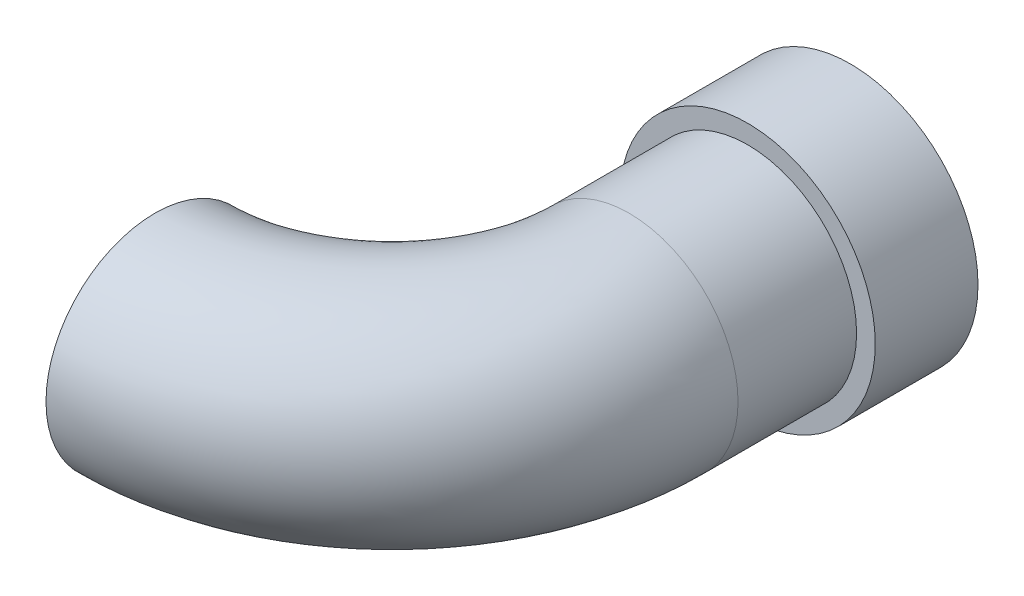
SolidWorks part; units mm, degrees
material "AISI 321 Annealed Stainless Steel (SS)"
ref_plane "Front Plane" through (0, 0, 0) normal (0, 0, 1) x (1, 0, 0)
ref_plane "Top Plane" through (0, 0, 0) normal (0, 1, 0) x (1, 0, 0)
ref_plane "Right Plane" through (0, 0, 0) normal (1, 0, 0) x (0, 0, -1)
sketch "Sketch1" plane through (0, 0, 0) normal (0, 0, 1) x (1, 0, 0)
  circle A0 centre (0, 0) radius 20.5
  circle A1 centre (0, 0) radius 17.5
  dimension "D1" = 41
  dimension "D2" = 3
extrude "Boss-Extrude1" add sketch "Sketch1" along normal blind 16.51
ref_plane "Plane1" through (0, 0, 10.16) normal (0, 0, 1) x (1, 0, 0)
sketch "Sketch2" plane through (0, 0, 10.16) normal (0, 0, 1) x (1, 0, 0)
  circle A0 centre (0, 0) radius 17.5
  circle A1 centre (0, 0) radius 15.5
  dimension "D1" = 2
  dimension "D2" = 35
sketch "Sketch4" plane through (0, 0, 10.16) normal (0, 0, 1) x (1, 0, 0)
  line L0 (0, 0) -> (-161.9875, 0) construction
  circle A0 centre (0, 0) radius 17.5
  circle A1 centre (0, 0) radius 15.5
  circle A2 centre (0, 0) radius 17.5 construction
  dimension "D1" = 2
sketch "Sketch5" plane through (0, 0, 0) normal (0, 1, 0) x (1, 0, 0)
  line L0 (0, -10.16) -> (0, -35.56)
  line L1 (-15.5, -10.16) -> (15.5, -10.16) construction
  arc A0 (0, -35.56) -> (-38.1, -73.66) centre (-38.1, -35.56) cw
  dimension "D2" = 38.1
  dimension "D1" = 25.4
sweep "Sweep3" add profiles "Sketch4" path "Sketch5"
